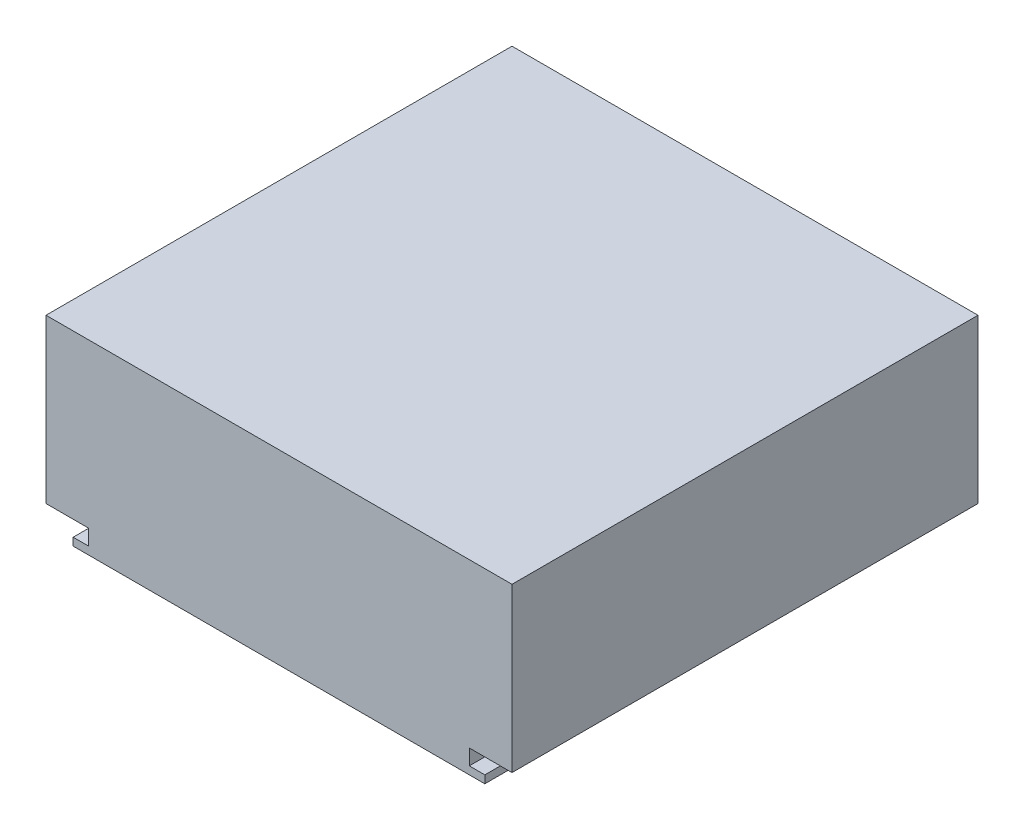
SolidWorks part; units mm, degrees
ref_plane "Front Plane" through (0, 0, 0) normal (0, 0, 1) x (1, 0, 0)
ref_plane "Top Plane" through (0, 0, 0) normal (0, 1, 0) x (1, 0, 0)
ref_plane "Right Plane" through (0, 0, 0) normal (1, 0, 0) x (0, 0, -1)
sketch "Sketch1" plane through (0, 0, 0) normal (0, 0, 1) x (1, 0, 0)
  line L0 (-26.5, 1) -> (-26.5, 0)
  line L1 (-30, 24) -> (30, 24)
  line L2 (-30, 24) -> (-30, 3)
  line L3 (-26.5, 0) -> (26.5, 0)
  line L4 (30, 24) -> (30, 3)
  line L5 (-30, 3) -> (-24.5, 3)
  line L7 (-26.5, 1) -> (-24.5, 1)
  line L8 (-24.5, 3) -> (-24.5, 1)
  line L9 (30, 3) -> (24.5, 3)
  line L11 (26.5, 1) -> (24.5, 1)
  line L12 (24.5, 3) -> (24.5, 1)
  line L13 (26.5, 1) -> (26.5, 0)
  point P12 (0, 0)
  dimension "D1" = 2
  dimension "D2" = 1
  dimension "D4" = 53
  dimension "D5" = 2
  dimension "D6" = 60
  dimension "D7" = 24
extrude "Boss-Extrude1" add sketch "Sketch1" along normal mid plane 60
sketch "Sketch2" plane through (0, 0, 0) normal (1, 0, 0) x (0, 0, -1)
  line L0 (-30, 3) -> (30, 3) construction
  line L1 (30, 3) -> (30, 24) construction
  line L2 (37.7933, 6.2247) -> (30, 24)
  line L3 (30, 24) -> (30, 0)
  line L5 (30, 24) -> (30, 3) construction
  line L8 (30, 0) -> (36.0155, 2.124)
  circle A0 centre (35, 5) radius 1.55
  arc A1 (37.7933, 6.2247) -> (36.0155, 2.124) centre (35, 5) cw
  dimension "D3" = 3.1
  dimension "D4" = 1.5
  dimension "D1" = 2
  dimension "D2" = 5
extrude "Boss-Extrude2" add sketch "Sketch2" along normal blind 5 from offset 2.175 contours L2 L3 A1
